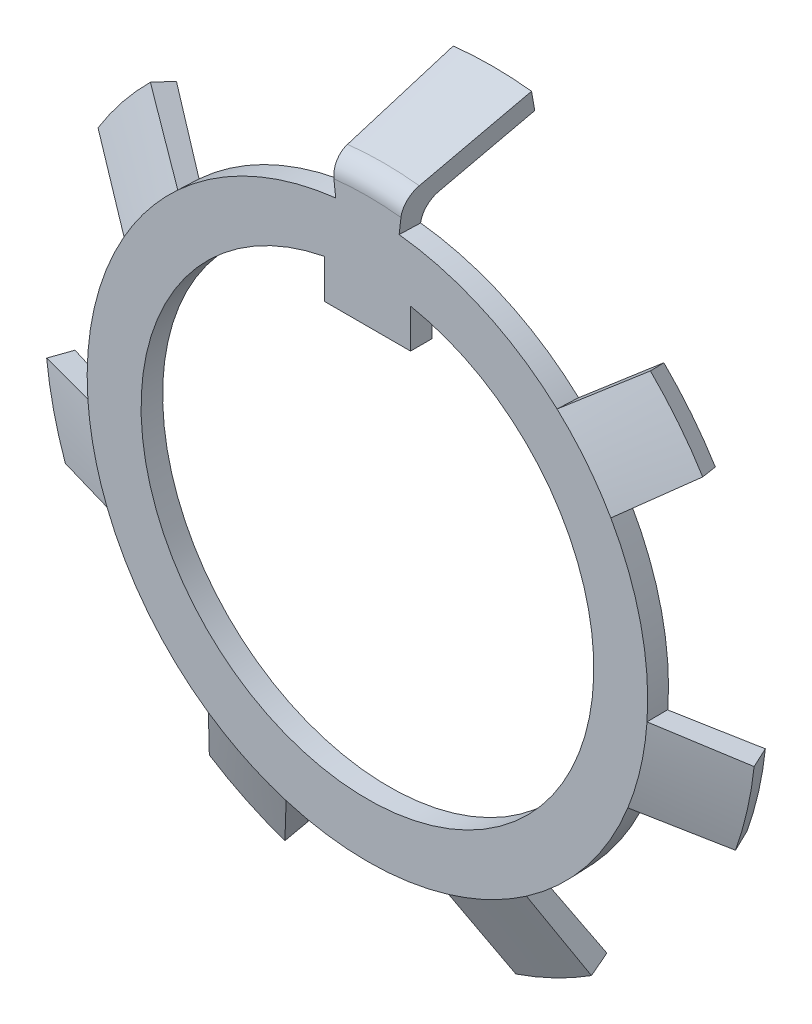
SolidWorks part; units mm, degrees
ref_plane "Front Plane" through (0, 0, 0) normal (0, 0, 1) x (1, 0, 0)
ref_plane "Top Plane" through (0, 0, 0) normal (0, 1, 0) x (1, 0, 0)
ref_plane "Right Plane" through (0, 0, 0) normal (1, 0, 0) x (0, 0, -1)
sketch "Sketch1" plane through (0, 0, 0) normal (1, 0, 0) x (0, 0, -1)
  line L0 (-1, 0) -> (23.0727, 0) construction
  line L1 (-1, 7.5) -> (-1, 13)
  line L2 (-1, 13) -> (0.529, 16.5)
  line L3 (0.529, 16.5) -> (1.4454, 16.0997)
  line L4 (1.4454, 16.0997) -> (0, 13)
  line L5 (0, 13) -> (0, 7.5)
  line L6 (0, 7.5) -> (-1, 7.5)
  dimension "D1" = 15
  dimension "D2" = 1
  dimension "D3" = 25
  dimension "D4" = 33
  dimension "D5" = 26
revolve "Revolve1" add sketch "Sketch1" angle 360 about L0
sketch "Sketch2" plane through (0, 0, 0) normal (0, 0, 1) x (1, 0, 0)
  line L0 (-2, 8.5) -> (-2, 10.3078)
  line L1 (-2, 8.5) -> (2, 8.5)
  line L5 (2, 8.5) -> (2, 10.3078)
  arc A0 (-2, 10.3078) -> (2, 10.3078) centre (0, 0) ccw
  point P1 (0, 8.5)
  dimension "D2" = 4
  dimension "D3" = 10.5
  dimension "D1" = 8.5
extrude "Cut-Extrude2" cut sketch "Sketch2" against normal through all both and the other way through all
sketch "Sketch3" plane through (0, 0, 1) normal (0, 0, 1) x (1, 0, 0)
  line L0 (0, 16.5) -> (0, 13) construction
  line L1 (14.0521, 8.6481) -> (11.2898, 6.4452)
  line L2 (2, 16.3783) -> (2, 12.8452)
  line L3 (-2, 16.3783) -> (-2, 12.8452)
  line L6 (11.5581, 11.7754) -> (8.7958, 9.5725)
  line L7 (15.5227, -5.5944) -> (12.0781, -4.8082)
  line L8 (16.4127, -1.6947) -> (12.9682, -0.9085)
  line L9 (5.3044, -15.6241) -> (3.7714, -12.4409)
  line L10 (8.9082, -13.8886) -> (7.3753, -10.7054)
  line L11 (-8.9082, -13.8886) -> (-7.3753, -10.7054)
  line L12 (-5.3044, -15.6241) -> (-3.7714, -12.4409)
  line L13 (-16.4127, -1.6947) -> (-12.9682, -0.9085)
  line L14 (-15.5227, -5.5944) -> (-12.0781, -4.8082)
  line L15 (-11.5581, 11.7754) -> (-8.7958, 9.5725)
  line L16 (-14.0521, 8.6481) -> (-11.2898, 6.4452)
  circle A0 centre (0, 0) radius 16.5 construction
  circle A1 centre (0, 0) radius 16.5
  circle A2 centre (0, 0) radius 13
  circle A3 centre (0, 0) radius 13 construction
  circle A4 centre (0, 0) radius 13
  circle A5 centre (0, 0) radius 13
  circle A6 centre (0, 0) radius 13
  circle A7 centre (0, 0) radius 13
  circle A8 centre (0, 0) radius 13
  circle A9 centre (0, 0) radius 13
  circle A10 centre (0, 0) radius 13 construction
  point P39 (0, 0)
  dimension "D2" = 4
  dimension "D1" = 7
extrude "Cut-Extrude4" cut sketch "Sketch3" against normal blind 10 draft 2
sketch "Sketch4" plane through (0, 0, 0) normal (1, 0, 0) x (0, 0, -1)
  line L0 (-1, 0) -> (23.0727, 0) construction
  line L1 (-1, 10) -> (-1, 14.5)
  line L2 (-1, 14.5) -> (4.7956, 16.0529)
  line L3 (4.7956, 16.0529) -> (5.0544, 15.087)
  line L4 (5.0544, 15.087) -> (0, 13.7327)
  line L5 (0, 13.7327) -> (0, 10)
  line L6 (0, 10) -> (-1, 10)
  dimension "D1" = 20
  dimension "D2" = 1
  dimension "D3" = 75
  dimension "D4" = 6
  dimension "D5" = 29
revolve "Revolve3" add sketch "Sketch4" angle 13 mid plane about L0
fillet "Fillet1" radius 1 2 edges at (0, 14.5, 1) (0, 13.7327, 0)
equation "\"d_ext_rouleau\"= 90"
equation "\"epaisseur_rouleau\"=80"
equation "\"alesage-rouleau\"= 52"
equation "\"jeu_dent_rouleau\"= 2"
equation "\"profondeur_dent_rouleau\"=4"
equation "\"n_dent_roueau\"= 15"
equation "\"d_ext_roulement_rouleau\"= 42"
equation "\"d_int_roulement_rouleau\"= 20"
equation "\"B_roulement_rouleau\"= 12"
equation "\"r_roulement_rouleau\"= 0.6"
equation "\"d_bille_roulement_rouleau\"= 8"
equation "\"F_anneau_alesage_rouleau\"=1.85"
equation "\"G_anneau_alesage_rouleau\"=47.5"
equation "\"K_anneau_alesage_rouleau\"=3.75"
equation "\"d_vis_flasque_rouleau\"=5"
equation "\"l-x_vis_flasque_rouleau\"=4"
equation "\"g_anneau_arbre_rouleau\"=19"
equation "\"f_anneau_arbre_rouleau\"=1.3"
equation "\"k_anneau_arbre_rouleau\"=1.5"
equation "\"entrax_vis_rouleau\"=65"
equation "\"d_granulat\"= 8"
equation "\"h_matrice\"= 22"
equation "\"d_matrice\"= 220"
equation "\"zone_vide_matrice\" = 48"
equation "\"d_alesage_matrice\"=20"
equation "\"a_clavette_alesage_matrice\"=6"
equation "\"B_roulement_matrice\"= 12"
equation "\"d_ext_roulement_matrice\"= 42"
equation "\"d_int_roulement_matrice\"= 20"
equation "\"r_roulement_matrice\"= 1"
equation "\"h_epaulement_arbre_matrice\" = 80"
equation "\"h_polie_matrice\" = 40"
equation "\"l_arbre_matrice\" = 300"
equation "\"d_int_ecrou_encouch_matrice\" = 20"
equation "\"d_ext_ecrou_encouch_matrice\" = 32"
equation "\"b_ecrou_encouch_matrice\" = 6"
equation "\"s_ecrou_encouch_matrice\" = 4"
equation "\"G_ecrou_encouch_matrice\" = 1"
equation "\"D2@Sketch1\"=\"G_ecrou_encouch_matrice\""
equation "\"D2@Sketch3\"=\"s_ecrou_encouch_matrice\""
equation "\"E_ecrou_encouch_matrice\" = 4"
equation "\"D2@Sketch2\"=\"E_ecrou_encouch_matrice\""
